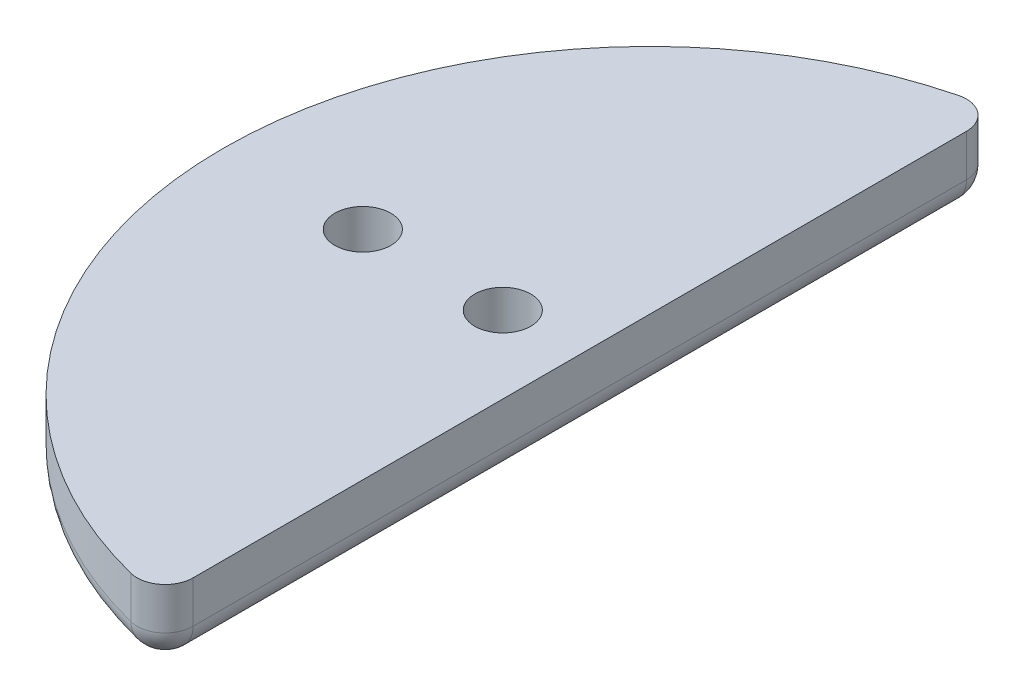
SolidWorks part; units mm, degrees
material "ABS"
ref_plane "Front Plane" through (0, 0, 0) normal (0, 0, 1) x (1, 0, 0)
ref_plane "Top Plane" through (0, 0, 0) normal (0, 1, 0) x (1, 0, 0)
ref_plane "Right Plane" through (0, 0, 0) normal (1, 0, 0) x (0, 0, -1)
sketch "Sketch2" plane through (0, 0, 0) normal (0, 1, 0) x (1, 0, 0)
  line L0 (-30.5, 0) -> (30.5, 0) construction
  line L1 (-5, 30.0874) -> (-5, -30.0874)
  arc A0 (-5, 30.0874) -> (-5, -30.0874) centre (0, 0) ccw
  point P5 (-20.5, 0)
  point P6 (-10.5, 0)
  dimension "D1" = 61
  dimension "D2" = 10
  dimension "D3" = 10
  dimension "D4" = 5
extrude "Boss-Extrude2" add sketch "Sketch2" along normal blind 5 contours A0 L1
sketch "Sketch3" plane through (0, 0, 0) normal (0, -1, 0) x (1, 0, 0)
  point P0 (-20.5, 0)
  point P1 (-10.5, 0)
hole_wizard "Ø4.0mm Dowel Hole1" positions "Sketch3" profile "Sketch4" hole size "Ø4.0" standard "ANSI Metric"
sketch "Sketch4" plane through (-20.5, 0, 0) normal (1, 0, 0) x (0, 0, -1)
  line L0 (0, 0) -> (0, 118.8308)
  line L1 (0, 118.8308) -> (2, 117.6291)
  line L2 (2, 117.6291) -> (2, 0)
  line L5 (2, 0) -> (0, 0)
  line L10 (0, 118.8308) -> (-2, 117.6291) construction
  line L11 (0, -6.35) -> (0, 107.95) construction
  dimension "Hole Dia." = 4
  dimension "Hole Depth" = 117.6291
  dimension "Drill Angle" = 118
fillet "Fillet1" radius 2 4 edges at (-30.5, 0, 0) (-5, 2.5, -30.0874) (-5, 2.5, 30.0874) (-5, 0, 0)
